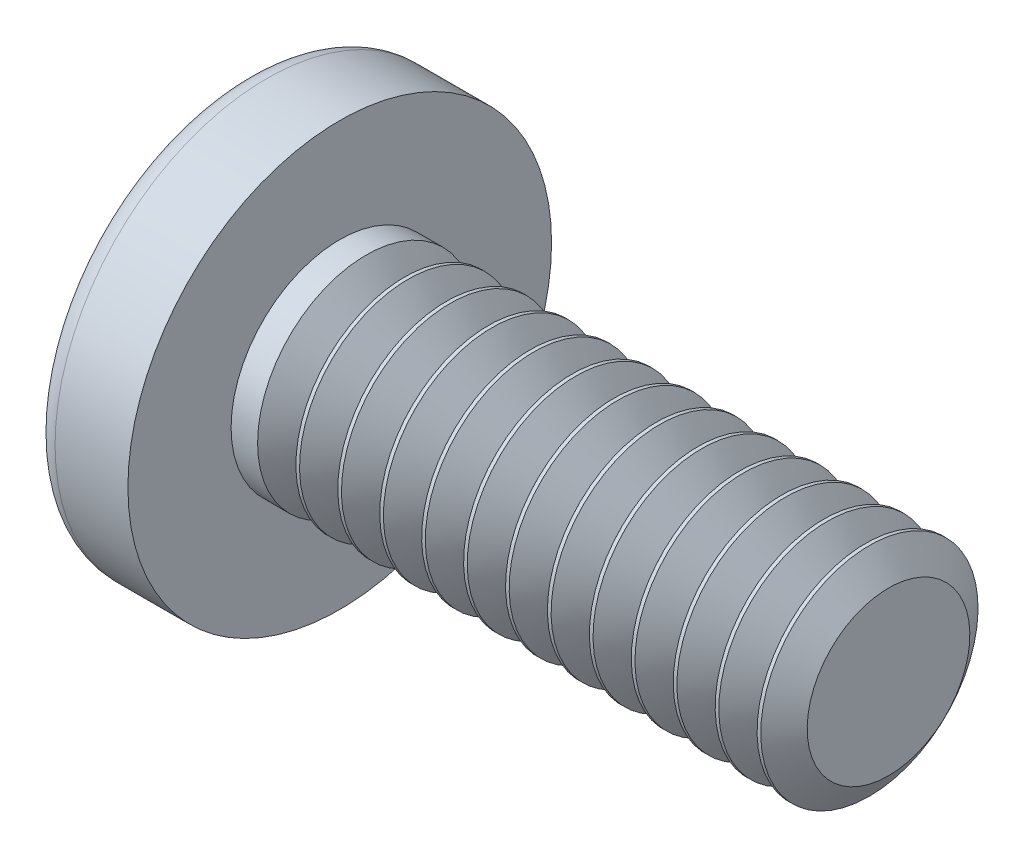
SolidWorks part; units mm, degrees
ref_plane "Plane1" through (0, 0, 0) normal (0, 0, 1) x (1, 0, 0)
ref_plane "Plane2" through (0, 0, 0) normal (0, 1, 0) x (1, 0, 0)
ref_plane "Plane3" through (0, 0, 0) normal (1, 0, 0) x (0, 0, -1)
other "Configuration Table"
sketch "BodySke" plane through (0, 0, 0) normal (0, 0, 1) x (1, 0, 0)
  line L0 (1.8034, 1.2573) -> (1.8034, 2.4511)
  line L1 (2.0676, 6.35) -> (2.0676, -3.175) construction
  line L2 (-25.4, 0) -> (127, 0) construction
  line L3 (8.1534, 0) -> (0, 0)
  line L4 (1.8034, 1.2573) -> (8.1534, 1.2573)
  line L5 (8.1534, 1.2573) -> (8.1534, 0)
  line L6 (0.9605, 2.4511) -> (1.8034, 2.4511)
  line L7 (1.8034, -1.2573) -> (8.1534, -1.2573) construction
  line L8 (1.8034, 6.35) -> (1.8034, -3.175) construction
  arc A0 (0.7542, 2.3452) -> (0, 0) centre (4.0234, 0) ccw
  arc A2 (0.7542, 2.3452) -> (0.9605, 2.4511) centre (0.9605, 2.1971) cw
  dimension "Head_crown_rad" = 4.0234
  dimension "Head_fillet_rad" = 0.254
  dimension "Diameter" = 2.5146
  dimension "Length" = 6.35
  dimension "Head_ht" = 1.8034
  dimension "Head_dia" = 4.9022
  dimension "Advance" = 0.5283
  dimension "Thread_nom" = 6.35
revolve "Base-Revolve" add sketch "BodySke" angle 360 about L2
cosmetic thread "ThreadCosmetic" [suppressed] parameters "Thread_length"=5.8217, "Thread_minor"=1.8821
sketch "Sketch3" plane through (0, 0, 0) normal (1, 0, 0) x (0, 0, -1)
  line L0 (0.3683, -1.5875) -> (-0.3683, -1.5875)
  line L1 (0.3683, -1.5875) -> (0.3683, 1.5875)
  line L2 (-0.3683, 1.5875) -> (0.3683, 1.5875)
  line L3 (-0.3683, 1.5875) -> (-0.3683, -1.5875)
  dimension "Cross_dia" = 3.175
  dimension "D1" = 1.5875
  dimension "Cross_width" = 0.7366
  dimension "D2" = 0.3683
ref_plane "Plane4" through (1.7526, 0, 0) normal (1, 0, 0) x (0, 0, -1)
sketch "Sketch4" plane through (1.7526, 0, 0) normal (1, 0, 0) x (0, 0, -1)
  line L0 (0.1842, -0.1842) -> (-0.1841, -0.1842)
  line L1 (0.1842, -0.1842) -> (0.1842, 0.1842)
  line L2 (-0.1842, 0.1842) -> (0.1842, 0.1842)
  line L3 (-0.1842, 0.1842) -> (-0.1841, -0.1842)
  dimension "D2" = 0.3683
  dimension "D1" = 0.3683
  dimension "D3" = 0.1842
  dimension "D4" = 0.1842
loft "Cut-Loft1" cut profiles "Sketch3", "Sketch4"
pattern_circular "CirPattern1" count 2 every 90 about axis through (0, 0, 0) along (1, 0, 0) of "Cut-Loft1"
sketch "ThdSchSke" plane through (0, 0, 0) normal (0, 0, 1) x (1, 0, 0)
  line L0 (2.3317, -0.9411) -> (2.1103, -1.2573)
  line L1 (2.3317, -0.9411) -> (2.5531, -1.2573)
  line L2 (2.5531, -1.2573) -> (2.5531, -1.5716)
  line L3 (-3.175, 0) -> (5.1513, 0) construction
  line L5 (2.5531, -1.5716) -> (2.1103, -1.5716)
  line L6 (2.1103, -1.5716) -> (2.1103, -1.2573)
  dimension "Diameter" = 2.5146
  dimension "SideAngle" = 55
  dimension "VeeAngle" = 70
  dimension "Thread_minor" = 1.8821
  dimension "Overcut" = 3.1432
  dimension "Start" = 2.3317
revolve "ThreadSchematic" cut sketch "ThdSchSke" angle 360 about L3
pattern_linear "ThdSchPat" count 13 spacing 0.4851 along (1, 0, 0) of "ThreadSchematic"
equation "\"D1@Sketch3\" = \"Cross_dia@Sketch3\" / 2"
equation "\"D2@Sketch3\" = \"Cross_width@Sketch3\" / 2"
equation "\"D1@Sketch4\" = \"Cross_width@Sketch3\" *.5"
equation "\"D2@Sketch4\" = \"D1@Sketch4\""
equation "\"D3@Sketch4\" = \"D1@Sketch4\" / 2"
equation "\"D4@Sketch4\" = \"D2@Sketch4\" / 2"
equation "\"Thread_length@ThreadCosmetic\" = ((sgn( (\"Length@BodySke\" - \"Advance@BodySke\" ) - \"Thread_nom@BodySke\" )-1)*( (\"Length@BodySke\" - \"Advance@BodySke\" ) - \"Thread_nom@BodySke\" ))/-2+ \"Thread_nom@BodySke\""
equation "\"Thread_minor@ThdSchSke\" = \"Thread_minor@ThreadCosmetic\""
equation "\"Diameter@ThdSchSke\" = \"Diameter@BodySke\""
equation "\"Overcut@ThdSchSke\" = \"Diameter@BodySke\" * 1.25"
equation "\"Start@ThdSchSke\" = \"Head_ht@BodySke\" + \"Length@BodySke\" - \"Thread_length@ThreadCosmetic\"  '---Non-countersunk---"
equation "\"Num_threads@ThdSchPat\" = int( \"Thread_length@ThreadCosmetic\" / \"Advance@BodySke\" + 0.999 )  + 1"
equation "\"Advance@ThdSchPat\" = \"Thread_length@ThreadCosmetic\" /  (\"Num_threads@ThdSchPat\" - 1) 'relax it"
